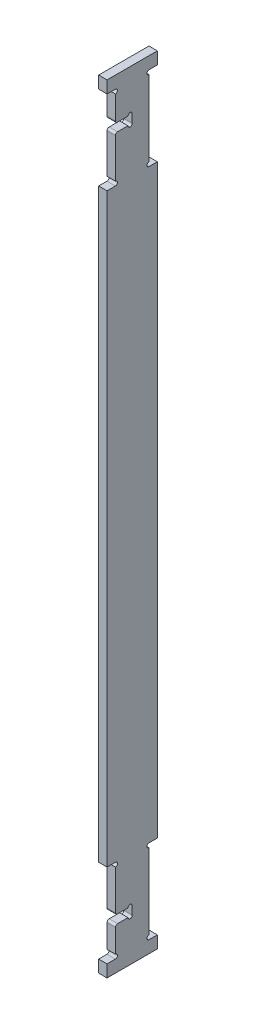
SolidWorks part; units mm, degrees
material "ABS"
ref_plane "Front Plane" through (0, 0, 0) normal (0, 0, 1) x (1, 0, 0)
ref_plane "Top Plane" through (0, 0, 0) normal (0, 1, 0) x (1, 0, 0)
ref_plane "Right Plane" through (0, 0, 0) normal (1, 0, 0) x (0, 0, -1)
sketch "Sketch2" plane through (0, 0, 0) normal (1, 0, 0) x (0, 0, -1)
  line L0 (-6, 0) -> (6, 0)
  line L1 (6, 0) -> (6, 69.865)
  line L2 (6, 69.865) -> (4, 69.865)
  line L3 (4, 70.865) -> (4, 88.865)
  line L4 (4, 89.865) -> (6, 89.865)
  line L5 (6, 89.865) -> (6, 92.7817)
  line L6 (6, 92.7817) -> (-6, 92.7817)
  line L7 (-6, 92.7817) -> (-6, 89.865)
  line L8 (-6, 89.865) -> (-4, 89.865)
  line L9 (-4, 88.865) -> (-4, 83.2997)
  line L10 (-3.5, 82.7997) -> (-1, 82.7997)
  line L11 (0, 82.7997) -> (0, 80.7997)
  line L12 (-1, 80.7997) -> (-3.5, 80.7997)
  line L13 (-4, 80.2997) -> (-4, 70.865)
  line L14 (-4, 69.865) -> (-6, 69.865)
  line L15 (-6, 69.865) -> (-6, 0)
  line L16 (55, 0) -> (-55, 0) construction
  line L19 (0, 44.2539) -> (0, -44.2539) construction
  arc A0 (4, 69.865) -> (4, 70.865) centre (4, 70.365) cw
  arc A1 (-4, 69.865) -> (-4, 70.865) centre (-4, 70.365) ccw
  arc A2 (0, 80.7997) -> (-1, 80.7997) centre (-0.5, 80.7997) cw
  arc A3 (0, 82.7997) -> (-1, 82.7997) centre (-0.5, 82.7997) ccw
  arc A4 (-4, 83.2997) -> (-3.5, 82.7997) centre (-3.5, 83.2997) ccw
  arc A5 (-3.5, 80.7997) -> (-4, 80.2997) centre (-3.5, 80.2997) ccw
  arc A6 (-4, 89.865) -> (-4, 88.865) centre (-4, 89.365) cw
  arc A7 (4, 89.865) -> (4, 88.865) centre (4, 89.365) ccw
  point P38 (4, 79.865)
  point P43 (0, 0)
  dimension "D1" = 12
  dimension "D2" = 8
  dimension "D3" = 4
  dimension "D4" = 2
  dimension "D5" = 79.865
  dimension "D6" = 20
  dimension "D7" = 2
extrude "Boss-Extrude1" add sketch "Sketch2" along normal blind 2
mirror "Mirror1" about plane through (0, 0, 0) normal (0, 1, 0) of "Boss-Extrude1"
